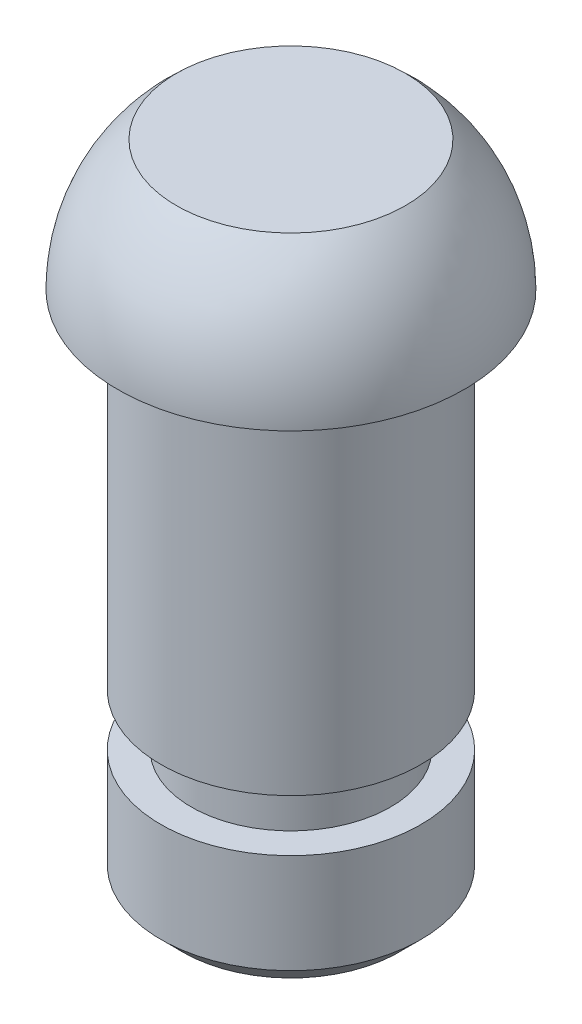
SolidWorks part; units mm, degrees
ref_plane "Front Plane" through (0, 0, 0) normal (0, 0, 1) x (1, 0, 0)
ref_plane "Top Plane" through (0, 0, 0) normal (0, 1, 0) x (1, 0, 0)
ref_plane "Right Plane" through (0, 0, 0) normal (1, 0, 0) x (0, 0, -1)
sketch "Sketch1" plane through (0, 0, 0) normal (0, 0, 1) x (1, 0, 0)
  line L0 (0, 0) -> (0, 6)
  line L2 (1.5, 6) -> (1.5, 2)
  line L3 (1.5, 2) -> (1.15, 2)
  line L4 (1.15, 2) -> (1.15, 1.4)
  line L5 (1.15, 1.4) -> (1.5, 1.4)
  line L6 (1.5, 1.4) -> (1.5, 0)
  line L7 (1.5, 0) -> (0, 0)
  line L8 (1.5, 6) -> (2, 6)
  line L9 (0, 7.5) -> (1.3229, 7.5)
  line L10 (0, 6) -> (0, 7.5)
  arc A1 (2, 6) -> (1.3229, 7.5) centre (0, 6) ccw
  dimension "D1" = 6
  dimension "D2" = 1.5
  dimension "D3" = 4
  dimension "D4" = 0.6
  dimension "D5" = 1.15
revolve "Revolve2" add sketch "Sketch1" angle 360 about L0
chamfer "Chamfer1" distance 0.25 angle 45 1 edges at (0, 0, -1.5)
